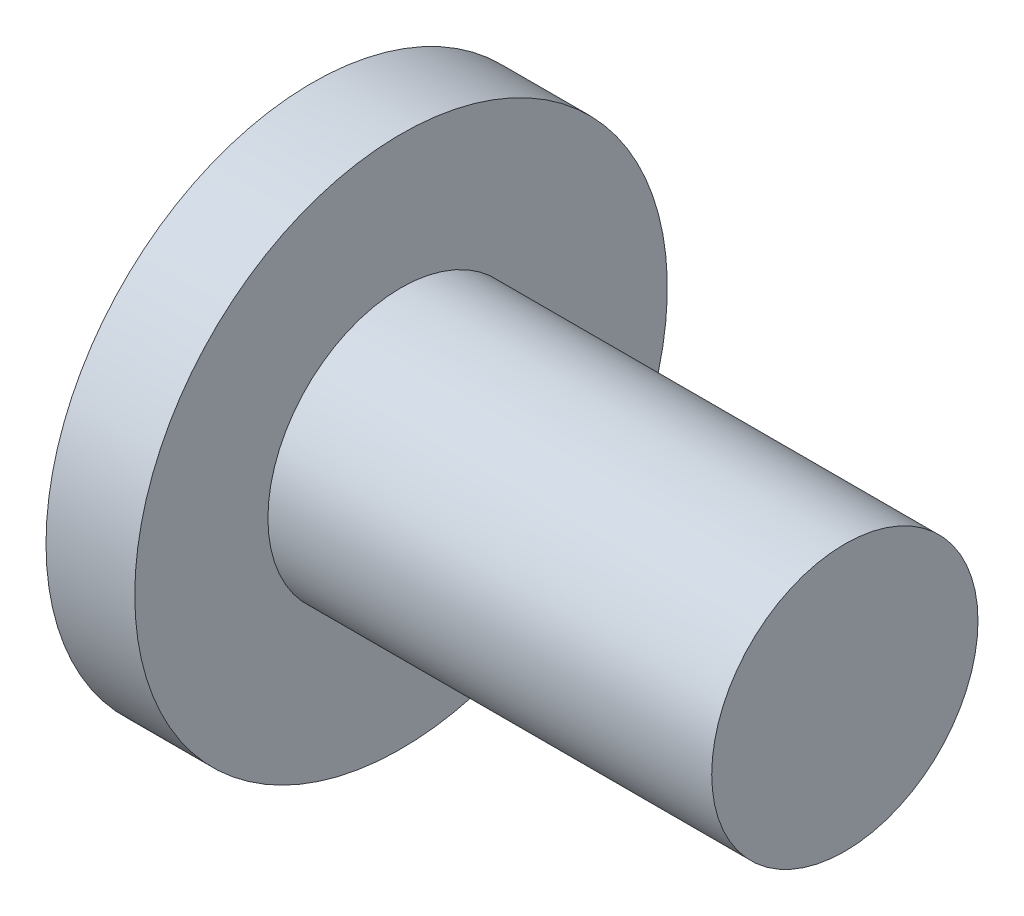
SolidWorks part; units mm, degrees
material "Cast Alloy Steel"
ref_plane "Front Plane" through (0, 0, 0) normal (0, 0, 1) x (1, 0, 0)
ref_plane "Top Plane" through (0, 0, 0) normal (0, 1, 0) x (1, 0, 0)
ref_plane "Right Plane" through (0, 0, 0) normal (1, 0, 0) x (0, 0, -1)
sketch "Sketch1" plane through (0, 0, 0) normal (0, 0, 1) x (1, 0, 0)
  line L0 (0, 0) -> (0, 3)
  line L1 (0, 3) -> (-10, 3)
  line L2 (-10, 3) -> (-10, 6)
  line L3 (-10, 6) -> (-12, 6)
  line L4 (-12, 6) -> (-12, 0)
  line L5 (-12, 0) -> (0, 0)
  dimension "D1" = 10
  dimension "D2" = 2
  dimension "D3" = 6
  dimension "D4" = 3
revolve "Revolve1" add sketch "Sketch1" angle 360 about L5
